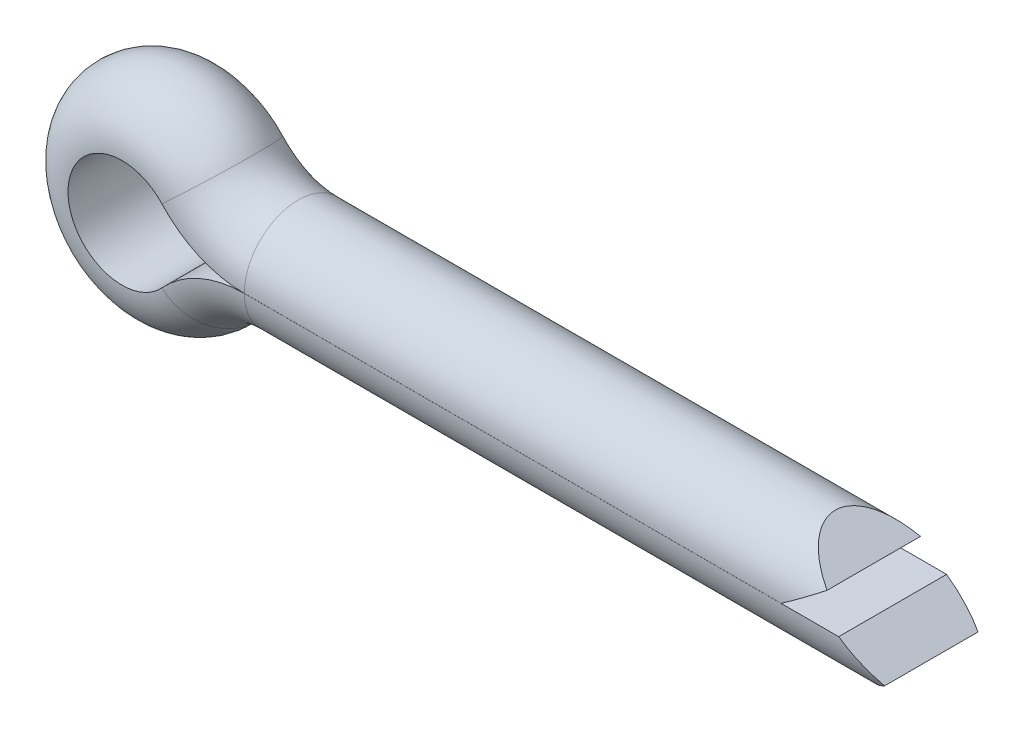
SolidWorks part; units mm, degrees
ref_plane "Front" through (0, 0, 0) normal (0, 0, 1) x (1, 0, 0)
ref_plane "Top" through (0, 0, 0) normal (0, 1, 0) x (1, 0, 0)
ref_plane "Right" through (0, 0, 0) normal (1, 0, 0) x (0, 0, -1)
sketch "PathSke" plane through (0, 0, 0) normal (0, 0, 1) x (1, 0, 0)
  line L0 (40, 3.75) -> (0, 3.75)
  line L1 (0, -3.75) -> (44, -3.75)
  line L2 (0, 0) -> (49.7718, 0) construction
  line L3 (0, 0) -> (0, 16.5256) construction
  line L4 (-16, 0) -> (-16, 14.2137) construction
  arc A0 (0, 3.75) -> (-2.9605, 5.0561) centre (0, 7.7583) cw
  arc A1 (-2.9605, 5.0561) -> (-2.9605, -5.0561) centre (-8.5, 0) ccw
  arc A2 (-2.9605, -5.0561) -> (0, -3.75) centre (0, -7.7583) cw
  dimension "Diameter" = 7.5
  dimension "Head_dia" = 15
  dimension "Head_ht" = 16
  dimension "Length" = 40
  dimension "Tip_offset" = 4
ref_plane "SectionPlane" through (40, 0, 0) normal (1, 0, 0) x (0, 0, -1)
sketch "SectionSke" plane through (40, 0, 0) normal (1, 0, 0) x (0, 0, -1)
  line L1 (-3.75, 0.002) -> (3.75, 0.002)
  arc A0 (3.75, 0.002) -> (-3.75, 0.002) centre (0, 0) ccw
  dimension "Diameter" = 7.5
  dimension "D1" = 0.002
sweep "Body" add profiles "SectionSke" path "PathSke"
sketch "ConeCutSke" plane through (0, 0, 0) normal (0, 0, 1) x (1, 0, 0)
  line L0 (0, 0) -> (0, 16.2682) construction
  line L1 (0, 0) -> (75.9079, 0) construction
  line L2 (0, 0) -> (44, 0) construction
  line L3 (40, 1.876) -> (37.3179, 3.76)
  line L4 (40, 0.002) -> (40, 3.75) construction
  line L6 (40, 1.876) -> (37.3123, 0)
  line L7 (44, -1.876) -> (41.3123, 0)
  line L8 (44, -3.75) -> (44, -0.002) construction
  line L9 (44, -1.876) -> (41.3179, -3.76)
  line L10 (41.3123, 0) -> (37.3123, 0)
  line L11 (37.3179, 3.76) -> (44.01, 3.76)
  line L12 (44.01, 3.76) -> (44.01, -3.76)
  line L13 (44.01, -3.76) -> (41.3179, -3.76)
  line L14 (40, 3.75) -> (0, 3.75) construction
  dimension "D1" = 0.01
  dimension "D2" = 0.01
  dimension "D3" = 70
  dimension "D4" = 70
extrude "ConeCut" cut sketch "ConeCutSke" against normal through all and the other way through all
equation "' \"Diameter@PathSke\" = 9.5"
equation "' \"Head_dia@PathSke\" = 19"
equation "' \"Head_ht@PathSke\" = 20"
equation "' \"Tip_offset@PathSke\" = 6.3"
equation "' \"Length@PathSke\" = 45"
equation "' \"Diameter@PathSke\" = 1"
equation "' \"Head_dia@PathSke\" = 2"
equation "' \"Head_ht@PathSke\" = 3"
equation "' \"Tip_offset@PathSke\" = 2.5"
equation "' \"Length@PathSke\" = 8"
equation "' \"Diameter@PathSke\" = 0.5"
equation "' \"Head_dia@PathSke\" = 1"
equation "' \"Head_ht@PathSke\" = 2"
equation "' \"Tip_offset@PathSke\" = 1.6"
equation "' \"Length@PathSke\" = 4"
equation "\"Diameter@SectionSke\" = \"Diameter@PathSke\""
equation "\"Length@SectionPlane\" = \"Length@PathSke\""
